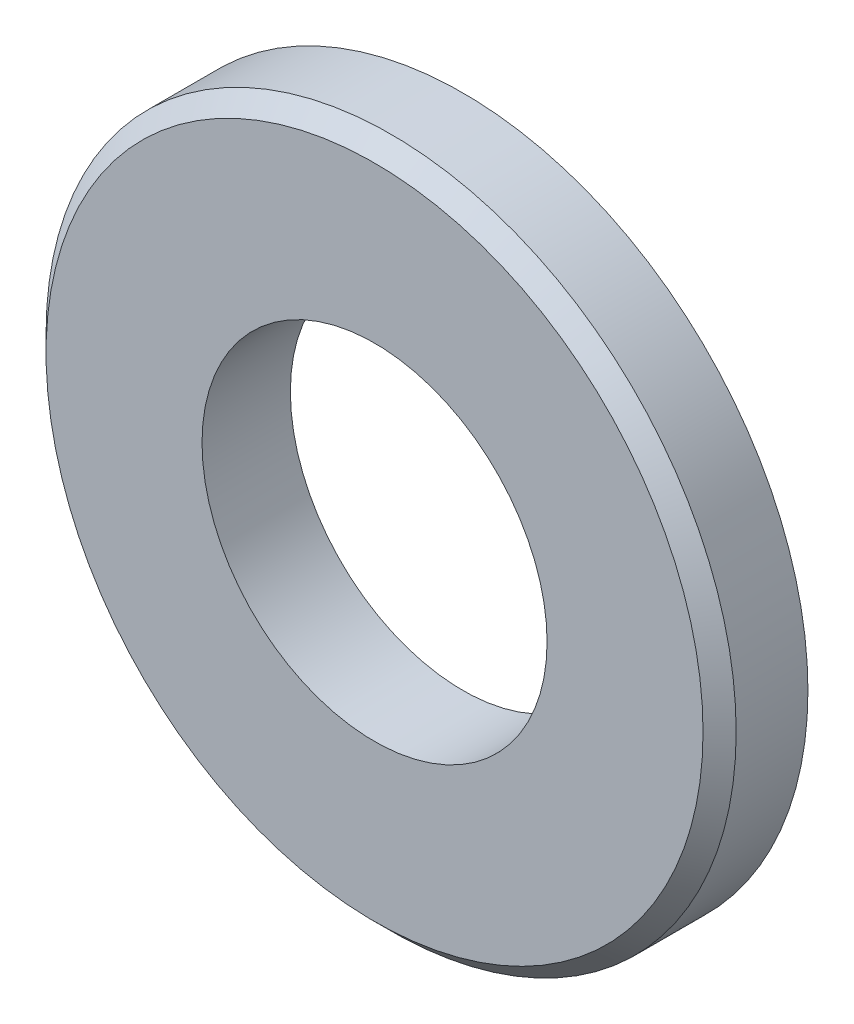
SolidWorks part; units mm, degrees
ref_plane "Alzado" through (0, 0, 0) normal (0, 0, 1) x (1, 0, 0)
ref_plane "Planta" through (0, 0, 0) normal (0, 1, 0) x (1, 0, 0)
ref_plane "Vista lateral" through (0, 0, 0) normal (1, 0, 0) x (0, 0, -1)
sketch "Croquis1" plane through (0, 0, 0) normal (0, 0, 1) x (1, 0, 0)
  circle A0 centre (0, 0) radius 3.125
  circle A1 centre (0, 0) radius 6.25
  dimension "D1" = 6.25
  dimension "D2" = 12.5
extrude "Saliente-Extruir1" add sketch "Croquis1" along normal blind 1.6
chamfer "Chaflán1" distance 0.3 angle 45 1 edges at (6.25, 0, 1.6)
